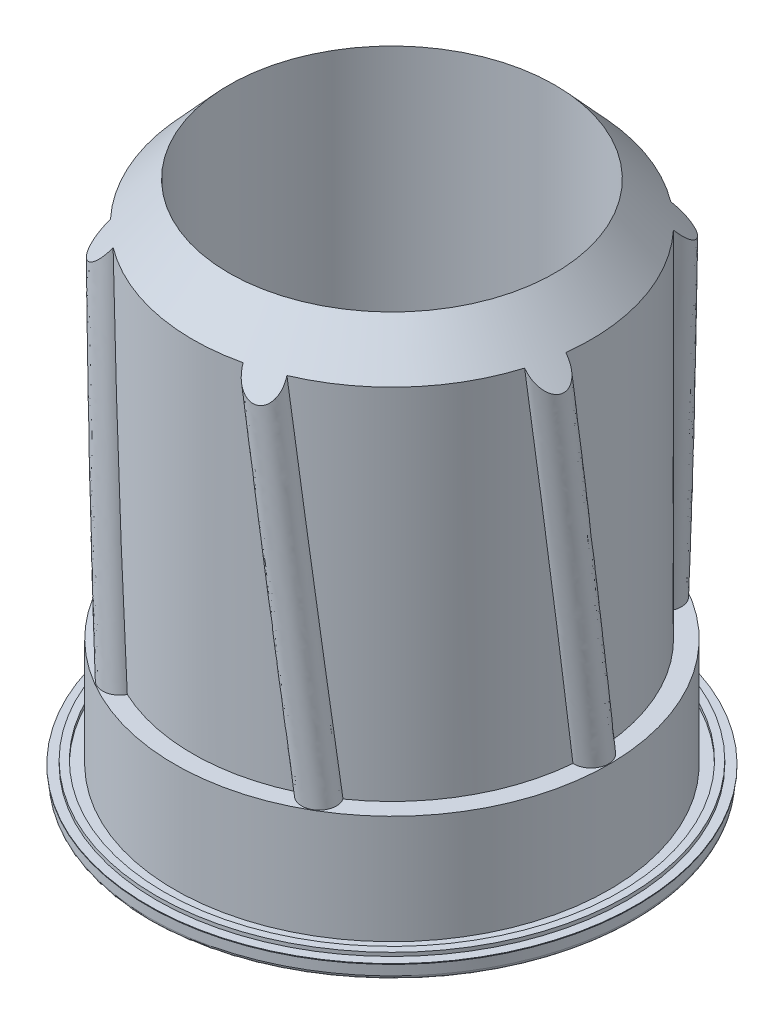
SolidWorks part; units mm, degrees
ref_plane "Alzado" through (0, 0, 0) normal (0, 0, 1) x (1, 0, 0)
ref_plane "Planta" through (0, 0, 0) normal (0, 1, 0) x (1, 0, 0)
ref_plane "Vista lateral" through (0, 0, 0) normal (1, 0, 0) x (0, 0, -1)
sketch "Croquis1" plane through (0, 0, 0) normal (0, 0, 1) x (1, 0, 0)
  line L0 (0, 0) -> (2.25, 0)
  line L1 (2.25, 0) -> (2.25, 7)
  line L2 (2.25, 7) -> (2.75, 7)
  line L3 (2.75, 7) -> (2.75, 1.5)
  line L4 (3, 0) -> (3.15, 0)
  line L5 (0, 0) -> (0, 19.6584) construction
  line L6 (3, 0) -> (3, 1.5)
  line L7 (3, 1.5) -> (2.75, 1.5)
  line L8 (3.15, 0) -> (3.15, 0.05)
  line L9 (3.15, 0.05) -> (3.25, 0.05)
  line L10 (3.25, 0.05) -> (3.25, 0)
  line L11 (3.25, 0) -> (3.35, 0)
  line L12 (0, -0.6573) -> (0, 0)
  line L13 (3.35, 0) -> (3.35, -0.2)
  line L14 (3.35, 0) -> (3.37, 0)
  line L15 (3.37, 0) -> (3.37, -0.01)
  line L16 (3.37, -0.01) -> (3.35, -0.01)
  arc A0 (0, -0.6573) -> (3.35, -0.2) centre (0, 11.8427) ccw
  circle A1 centre (2.9587, -0.005) radius 0.005
  dimension "D11" = 25
  dimension "D2" = 0.05
  dimension "D3" = 0.5
  dimension "D4" = 2.75
  dimension "D5" = 0.01
  dimension "D6" = 0.25
  dimension "D7" = 7
  dimension "D8" = 3.15
  dimension "D9" = 0.1
  dimension "D10" = 3.35
  dimension "D12" = 0.02
  dimension "D13" = 0.2
revolve "Revolución1" add sketch "Croquis1" angle 360 about L5
sketch "Croquis2" plane through (0, 1.5, 0) normal (0, 1, 0) x (1, 0, 0)
  arc A0 (2.7395, -0.2397) -> (2.7395, 0.2397) centre (2.75, 0) ccw
  arc A2 (2.7395, -0.2397) -> (2.7395, 0.2397) centre (0, 0) ccw
ref_axis "Eje1" through (0, 7, 0) along (0, -1, 0)
sketch "Croquis6" plane through (0, 1.5, 0) normal (0, 1, 0) x (1, 0, 0)
  circle A0 centre (0, 0) radius 2.75
curve "Hélice/Espiral1" pitch 150 height 5 turns 0.0333
sweep "Barrer1" add profiles "Croquis2" path "Hélice/Espiral1"
pattern_circular "MatrizC1" count 6 over 360 about axis through (0, 7, 0) along (0, -1, 0) of "Barrer1"
fillet "Redondeo1" radius 0.05 1 edges at (0, -0.2, -3.35)
sketch "Croquis7" plane through (0, 0, 0) normal (0, 0, 1) x (1, 0, 0)
  line L0 (2.25, 7) -> (3.4371, 5.7045)
  line L1 (3.4371, 5.7045) -> (3.4371, 7)
  line L2 (3.4371, 7) -> (2.25, 7)
  dimension "D1" = 47.5
revolve "Cortar-Revolución1" cut sketch "Croquis7" angle 360 about L5
